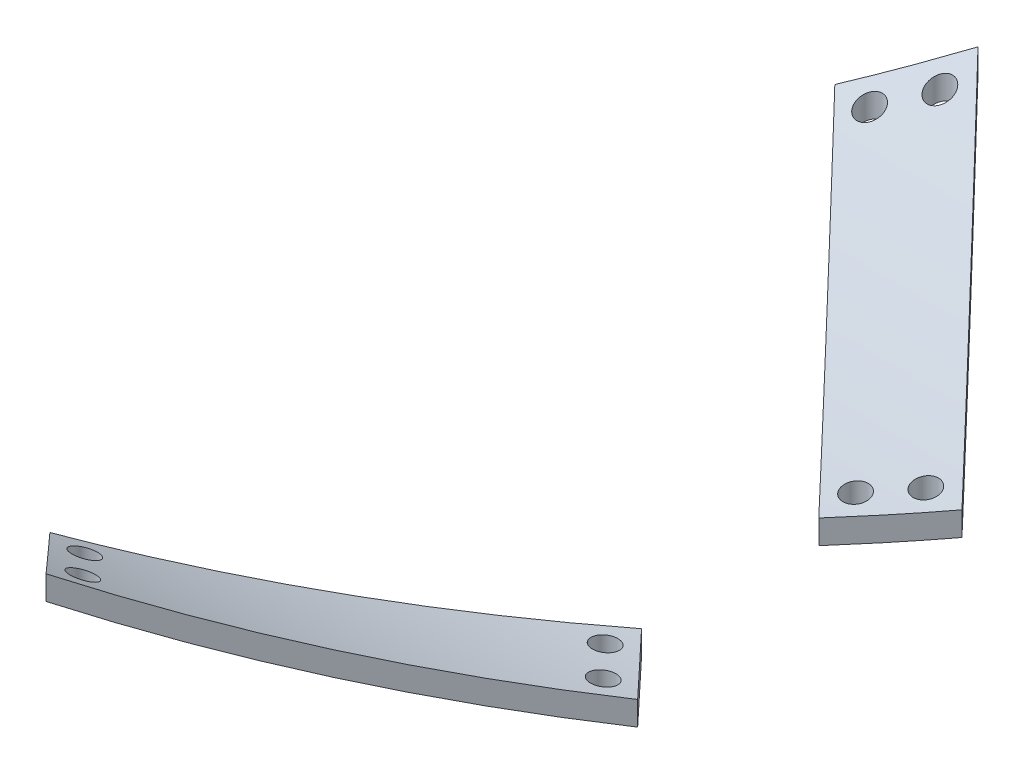
SolidWorks part; units mm, degrees
ref_plane "Front Plane" through (0, 0, 0) normal (0, 0, 1) x (1, 0, 0)
ref_plane "Top Plane" through (0, 0, 0) normal (0, 1, 0) x (1, 0, 0)
ref_plane "Right Plane" through (0, 0, 0) normal (1, 0, 0) x (0, 0, -1)
sketch "Sketch3" plane through (0, 0, 0) normal (1, 0, 0) x (0, 0, -1)
  line L0 (-8.3933, 1.9614) -> (-8.3933, -4.052)
  line L6 (-8.3933, -4.3886) -> (-8.3933, 1.9614)
  line L8 (232.9067, -4.3886) -> (232.9067, 1.9614)
  line L9 (232.9067, -4.052) -> (232.9067, 1.9614)
  arc A2 (-8.3933, 1.9614) -> (232.9067, 1.9614) centre (112.2567, 210.9333) ccw
  arc A3 (-8.3933, -4.052) -> (232.9067, -4.052) centre (112.2567, 204.9199) ccw
  dimension "D1" = 6.35
  dimension "D2" = 241.3
extrude "Boss-Extrude4" add sketch "Sketch3" along normal blind 304.8 contours L0 A3 L8 A2
ref_plane "Plane1" through (0, 1.9614, 0) normal (0, 1, 0) x (1, 0, 0)
sketch "Sketch5" plane through (0, 1.9614, 0) normal (0, 1, 0) x (1, 0, 0)
  line L0 (226.8283, 228.1486) -> (299.0035, 151.9486)
  line L1 (282.575, 88.0193) -> (300.0419, 69.5784)
  line L4 (226.8283, 228.1486) -> (208.3874, 210.6817)
  line L5 (299.0035, 151.9486) -> (280.5626, 134.4817)
  line L6 (208.3874, 210.6817) -> (280.5626, 134.4817)
  line L7 (206.375, 15.8441) -> (223.8419, -2.5968)
  line L8 (206.375, 15.8441) -> (282.575, 88.0193)
  line L9 (223.8419, -2.5968) -> (300.0419, 69.5784)
  point P0 (244.475, 51.9317)
  point P14 (244.475, 172.5817)
  point P15 (244.475, 51.9317)
  point P16 (244.475, 172.5817)
  dimension "D1" = 25.4
  dimension "D2" = 76.2
extrude "Cut-Extrude1" cut sketch "Sketch5" against normal blind 304.8 flip side to cut
sketch "Sketch6" plane through (0, 1.9614, 0) normal (0, 1, 0) x (1, 0, 0)
  line L0 (223.8419, -2.5968) -> (206.375, 15.8441)
  line L1 (223.8419, -2.5968) -> (300.088, 69.6221)
  line L2 (206.375, 15.8441) -> (282.6211, 88.063)
  line L3 (300.088, 69.6221) -> (282.6211, 88.063)
  line L8 (215.1085, 6.6236) -> (291.3546, 78.8425)
  line L9 (223.8419, -2.5968) -> (219.4752, 2.0134)
  line L10 (223.8419, -2.5968) -> (228.4521, 1.7699)
  line L11 (219.4752, 2.0134) -> (224.0854, 6.3801)
  line L12 (228.4521, 1.7699) -> (224.0854, 6.3801)
  line L13 (261.965, 33.5126) -> (244.4981, 51.9535)
  line L14 (289.6965, 143.1331) -> (217.5213, 219.3331)
  line L16 (280.5626, 134.4817) -> (276.1959, 139.0919)
  circle A0 centre (224.0854, 6.3801) radius 3.175
  circle A1 centre (215.352, 15.6006) radius 3.175
  circle A2 centre (282.3776, 79.0861) radius 3.175
  circle A3 centre (291.1111, 69.8656) radius 3.175
  circle A5 centre (280.686, 143.5821) radius 3.175
  circle A8 centre (289.7367, 152.1547) radius 3.175
  circle A9 centre (226.5317, 218.8842) radius 3.175
  circle A10 centre (217.481, 210.3116) radius 3.175
  point P30 (0, 0)
  point P39 (0, 0)
  dimension "D3" = 6.35
  dimension "D1" = 6.35
  dimension "D2" = 6.35
extrude "Cut-Extrude2" cut sketch "Sketch6" against normal blind 304.8 contours A0 | A1 | A3 | A2 | A5 | A8 | A9 | A10
